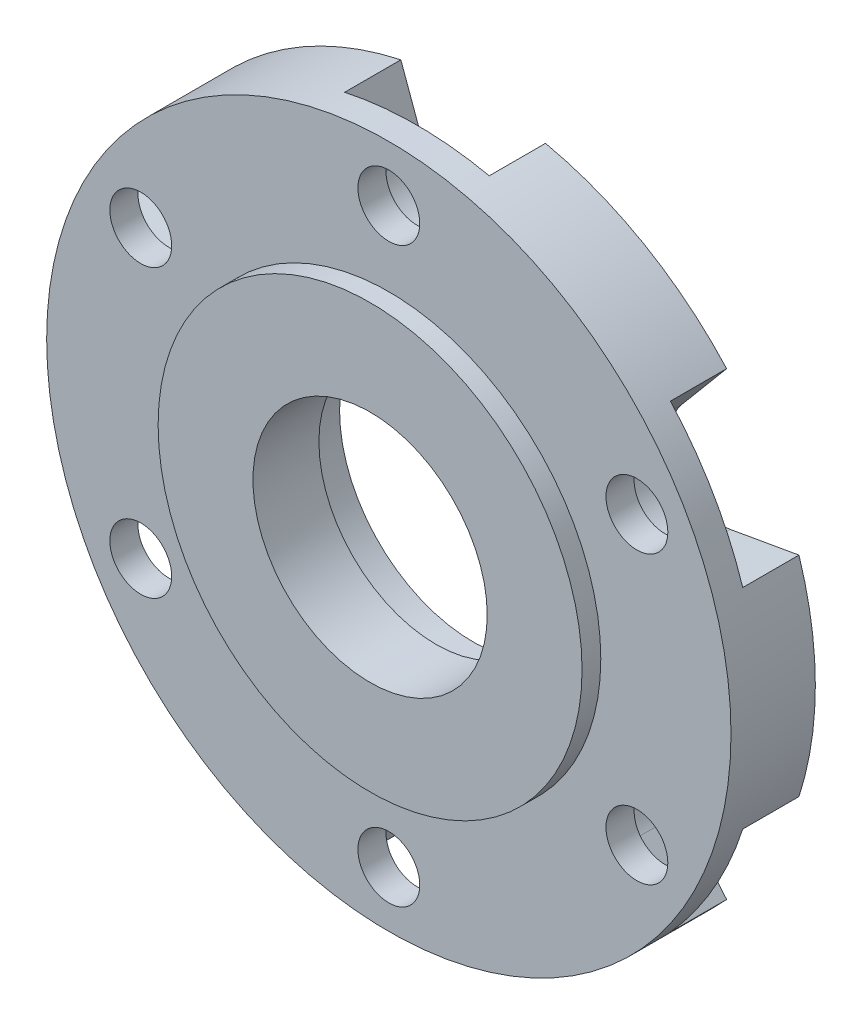
SolidWorks part; units mm, degrees
material "6061-T6 (SS)"
ref_plane "Front Plane" through (0, 0, 0) normal (0, 0, 1) x (1, 0, 0)
ref_plane "Top Plane" through (0, 0, 0) normal (0, 1, 0) x (1, 0, 0)
ref_plane "Right Plane" through (0, 0, 0) normal (1, 0, 0) x (0, 0, -1)
sketch "Sketch Spindle Skeleton" plane through (0, 0, 0) normal (1, 0, 0) x (0, 0, -1)
  line L0 (-95.847, -9.525) -> (-140.95, -9.525)
  line L5 (-1000, 0) -> (49000, 0)
  line L6 (0, -9.525) -> (0, 9.525)
  line L13 (0, 9.525) -> (-45.847, 9.525)
  line L26 (-45.847, 9.525) -> (-45.847, 14)
  line L27 (-45.847, 14) -> (-95.847, 14)
  line L32 (-95.847, 14) -> (-95.847, 9.525)
  line L34 (-160, 7) -> (-160, -7)
  line L36 (-95.847, -9.525) -> (-95.847, -14)
  line L37 (-95.847, -14) -> (-45.847, -14)
  line L38 (-45.847, -14) -> (-45.847, -9.525)
  line L39 (0, -9.525) -> (-45.847, -9.525)
  line L40 (-25.305, 36.5125) -> (-16.305, 36.5125)
  line L41 (-111.341, 22.6187) -> (-95.847, 22.6187)
  line L42 (-111.341, 22.6187) -> (-111.341, -22.6187)
  line L43 (-111.341, -22.6187) -> (-95.847, -22.6187)
  line L44 (-95.847, 22.6187) -> (-95.847, -22.6187)
  line L45 (-111.341, 22.6187) -> (-95.847, -22.6187) construction
  line L46 (-111.341, -22.6187) -> (-95.847, 22.6187) construction
  line L47 (-30.353, 22.6187) -> (-45.847, 22.6187)
  line L48 (-30.353, 22.6187) -> (-30.353, -22.6187)
  line L49 (-30.353, -22.6187) -> (-45.847, -22.6187)
  line L50 (-45.847, 22.6187) -> (-45.847, -22.6187)
  line L51 (-30.353, 22.6187) -> (-45.847, -22.6187) construction
  line L52 (-30.353, -22.6187) -> (-45.847, 22.6187) construction
  line L59 (-16.305, 36.5125) -> (-16.305, -36.5125)
  line L60 (-16.305, -36.5125) -> (-25.305, -36.5125)
  line L61 (-25.305, -22.6187) -> (-27.305, -22.6187)
  line L62 (-27.305, -22.6187) -> (-27.305, -12.5)
  line L63 (-27.305, -12.5) -> (-25.305, -12.5)
  line L64 (-25.305, -12.5) -> (-25.305, 12.5)
  line L65 (-25.305, 12.5) -> (-27.305, 12.5)
  line L66 (-27.305, 12.5) -> (-27.305, 22.6187)
  line L67 (-27.305, 22.6187) -> (-25.305, 22.6187)
  line L68 (-25.305, 22.6187) -> (-25.305, 36.5125)
  line L69 (-25.305, -22.6187) -> (-25.305, -36.5125)
  line L71 (-119.469, 36.5125) -> (-26.305, 36.5125)
  line L72 (-119.469, 36.5125) -> (-119.469, -36.5125)
  line L73 (-119.469, -36.5125) -> (-26.305, -36.5125)
  line L74 (-26.305, 36.5125) -> (-26.305, -36.5125)
  line L75 (-119.469, 36.5125) -> (-26.305, -36.5125) construction
  line L76 (-119.469, -36.5125) -> (-26.305, 36.5125) construction
  line L77 (-140.95, -9.525) -> (-140.95, -7)
  line L78 (-140.95, -7) -> (-160, -7)
  line L79 (-95.847, 9.525) -> (-140.95, 9.525)
  line L80 (-140.95, 7) -> (-160, 7)
  line L81 (-140.95, 9.525) -> (-140.95, 7)
  line L82 (-118.3985, 9.525) -> (-118.3985, -9.525) construction
  line L83 (-22.9235, 9.525) -> (-22.9235, -9.525) construction
  line L96 (-119.469, 36.5125) -> (-134.709, 36.5125)
  line L98 (-119.469, -36.5125) -> (-134.709, -36.5125)
  line L99 (-134.709, 36.5125) -> (-134.709, -36.5125)
  line L110 (-119.469, 36.5125) -> (-119.469, -36.5125)
  point P3 (0, 0)
  point P18 (-103.594, 0)
  point P24 (-38.1, 0)
  point P29 (-72.887, 0)
  point P48 (-16.305, 30.5656)
  point P58 (0, 0)
  point P59 (0, 0)
  point P70 (-134.709, 31.75)
revolve "Main Revolve" add sketch "Sketch Spindle Skeleton" angle 360 about L5
sketch "Sketch Center Cut" plane through (0, 0, 25.305) normal (0, 0, 1) x (1, 0, 0)
  circle A3 centre (0, 0) radius 12.5
  dimension "D1" = 25
extrude "Cut Center" cut sketch "Sketch Center Cut" against normal through all both and the other way through all
hole_wizard "CBORE for M6 SHCS1" positions "Hole wizard sketch 1" profile "Hole wizard sketch 2" counterbore size "M6" standard "ANSI Metric" end condition through all
sketch "Hole wizard sketch 1" plane through (0, 0, 16.305) normal (0, 0, -1) x (-1, 0, 0)
  point P0 (0, 30.5656)
sketch "Hole wizard sketch 2" plane through (0, 30.5656, 16.305) normal (1, 0, 0) x (0, 1, 0)
  line L0 (0, 0) -> (0, 11)
  line L1 (0, 11) -> (3.3, 11)
  line L3 (3.3, 11) -> (3.3, 6)
  line L4 (3.3, 6) -> (5.5, 6)
  line L5 (5.5, 6) -> (5.5, 0)
  line L7 (5.5, 0) -> (0, 0)
  line L11 (0, -6.35) -> (0, 107.95) construction
  dimension "Thru Hole Dia." = 6.6
  dimension "Thru Hole Depth" = 11
  dimension "C'Bore Dia." = 11
  dimension "C'Bore Depth" = 6
pattern_circular "CirPattern1" count 6 over 360 about axis through (0, 0, 0) along (0, 0, 1) of "CBORE for M6 SHCS1"
sketch "Sketch1" plane through (0, 0, 16.305) normal (0, 0, -1) x (-1, 0, 0)
  circle A0 centre (0, 0) radius 14.2558
  dimension "D1" = 28.5115
extrude "Cut-Extrude1" cut sketch "Sketch1" against normal blind 3.9624
sketch "Sketch2" plane through (0, 0, 16.305) normal (0, 0, -1) x (-1, 0, 0)
  line L0 (-5.1683, 28.6845) -> (-7.7172, 35.6876)
  line L1 (0, 30.5656) -> (0, 37.65) construction
  line L2 (5.1683, 28.6845) -> (7.7172, 35.6876)
  circle A0 centre (0, 30.5656) radius 5.5 construction
  circle A1 centre (0, 0) radius 36.5125 construction
  arc A2 (-5.1683, 28.6845) -> (5.1683, 28.6845) centre (0, 30.5656) ccw
  point P37 (0.065, 0.0375)
  circle M8 centre (0, 30.5656) radius 5.5
  circle M9 centre (0, 0) radius 36.5125
  dimension "D1" = 20
extrude "Cut-Extrude2" cut sketch "Sketch2" against normal up to surface (6 mm away) contours L1 L2 M8 M9 | L1 L0 M8 M9 up to face at (23.1706, -15.2828, 22.305)
pattern_circular "CirPattern2" count 6 over 360 about axis through (0, 0, 0) along (0, 0, 1) of "Cut-Extrude2"
